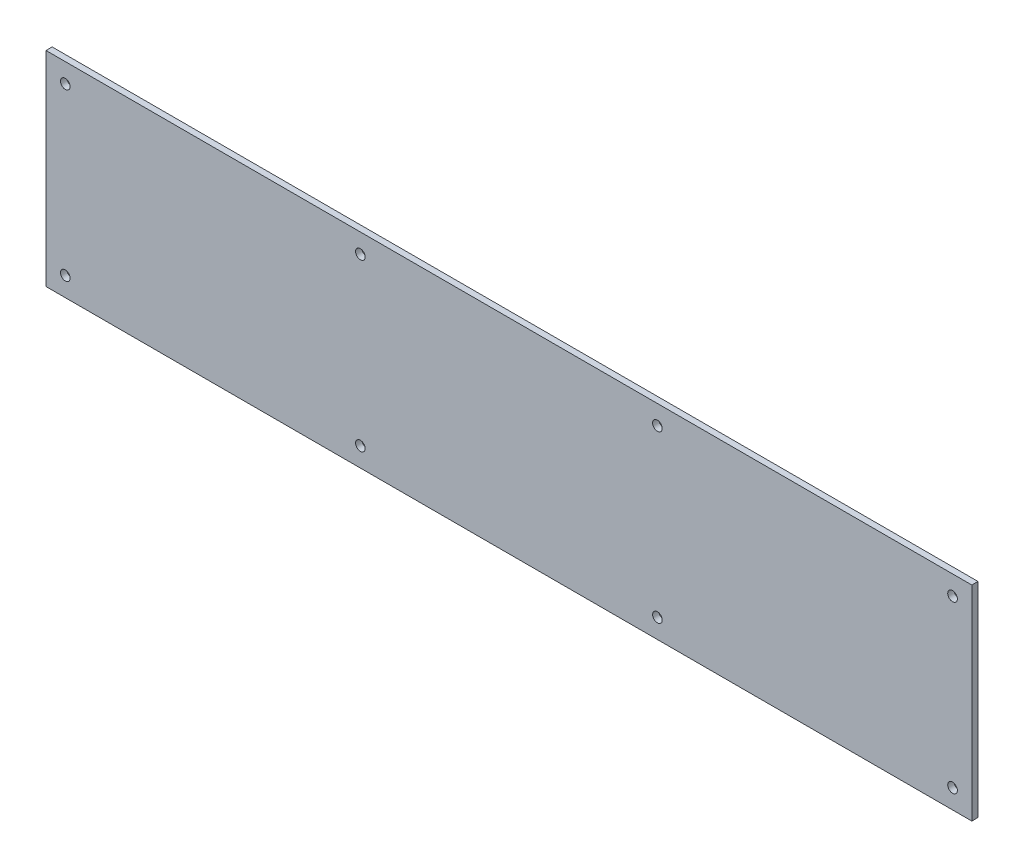
SolidWorks part; units mm, degrees
material "Acrylic (Medium-high impact)"
ref_plane "Front Plane" through (0, 0, 0) normal (0, 0, 1) x (1, 0, 0)
ref_plane "Top Plane" through (0, 0, 0) normal (0, 1, 0) x (1, 0, 0)
ref_plane "Right Plane" through (0, 0, 0) normal (1, 0, 0) x (0, 0, -1)
sketch "Sketch1" plane through (0, 0, 0) normal (0, 0, 1) x (1, 0, 0)
  line L0 (0, 215.9) -> (0, 142.24) construction
  line L1 (-304.8, 228.6) -> (0, 228.6)
  line L2 (-304.8, 228.6) -> (-304.8, 161.29)
  line L3 (-304.8, 161.29) -> (0, 161.29)
  line L4 (0, 228.6) -> (0, 161.29)
  line L5 (0, 142.24) -> (-304.8, 142.24) construction
  dimension "D1" = 19.05
extrude "Extrude1" add sketch "Sketch1" along normal blind 2.032
sketch "Sketch2" plane through (0, 0, 2.032) normal (0, 0, 1) x (1, 0, 0)
  line L0 (-152.4, 228.6) -> (-152.4, 118.3629) construction
  line L2 (-298.45, 222.25) -> (-298.45, 155.4628) construction
  line L3 (-304.8, 167.64) -> (0, 167.64)
  line L4 (-304.8, 167.64) -> (-25.4, 167.64) construction
  line L5 (-201.295, 222.25) -> (-201.295, 154.3861) construction
  circle A0 centre (-201.295, 222.25) radius 1.5875 construction
  circle A1 centre (-298.45, 222.25) radius 1.5875 construction
  circle A2 centre (-201.295, 222.25) radius 1.5875
  circle A3 centre (-298.45, 222.25) radius 1.5875
  circle A4 centre (-298.45, 167.64) radius 1.5875
  circle A5 centre (-201.295, 167.64) radius 1.5875
  circle A6 centre (-103.505, 167.64) radius 1.5875
  circle A7 centre (-6.35, 167.64) radius 1.5875
  circle A8 centre (-6.35, 222.25) radius 1.5875
  circle A9 centre (-103.505, 222.25) radius 1.5875
  dimension "D1" = 6.35
extrude "Cut-Extrude1" cut sketch "Sketch2" against normal through all
